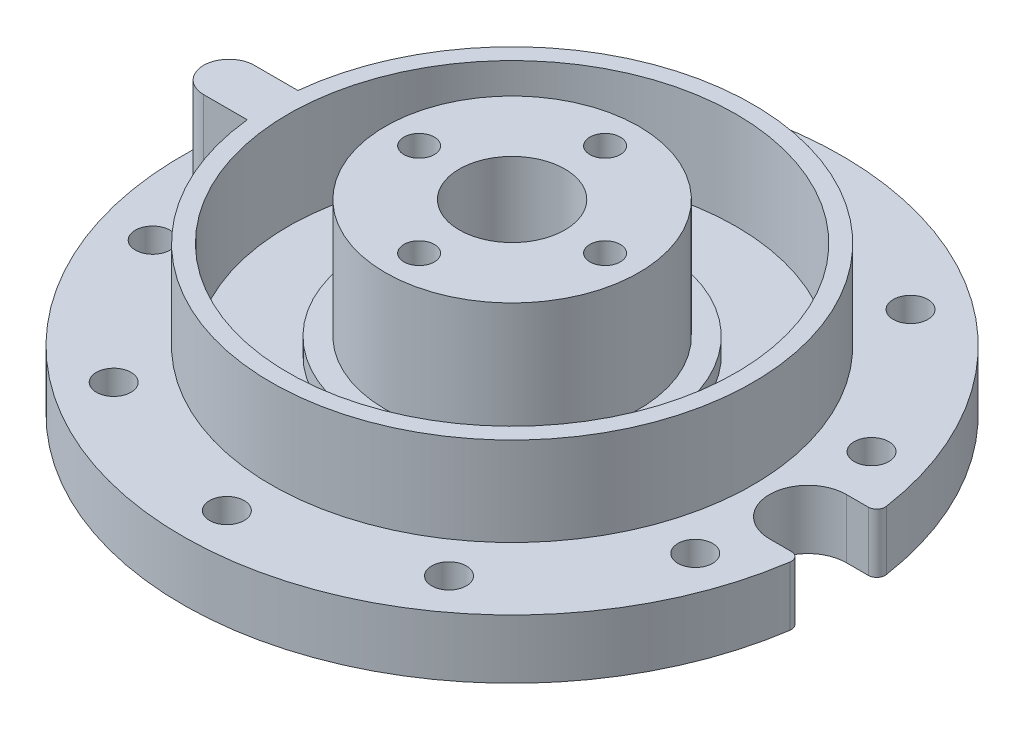
SolidWorks part; units mm, degrees
ref_plane "Front Plane" through (0, 0, 0) normal (0, 0, 1) x (1, 0, 0)
ref_plane "Top Plane" through (0, 0, 0) normal (0, 1, 0) x (1, 0, 0)
ref_plane "Right Plane" through (0, 0, 0) normal (1, 0, 0) x (0, 0, -1)
sketch "Sketch1" plane through (0, 0, 0) normal (0, 1, 0) x (1, 0, 0)
  circle A0 centre (0, 0) radius 39
  dimension "D1" = 78
extrude "Boss-Extrude1" add sketch "Sketch1" along normal blind 7
sketch "Sketch3" plane through (0, 7, 0) normal (0, 1, 0) x (1, 0, 0)
  circle A0 centre (0, 0) radius 17.5
  dimension "D1" = 35
extrude "Boss-Extrude2" add sketch "Sketch3" along normal blind 1
sketch "Sketch4" plane through (0, 8, 0) normal (0, 1, 0) x (1, 0, 0)
  circle A0 centre (0, 0) radius 15
  dimension "D1" = 30
extrude "Boss-Extrude3" add sketch "Sketch4" along normal blind 14 contours A0
sketch "Sketch5" plane through (0, 22, 0) normal (0, 1, 0) x (1, 0, 0)
  circle A0 centre (0, 0) radius 6.25
  circle A1 centre (0, 11) radius 1.8
  circle A2 centre (11, 0) radius 1.8
  circle A3 centre (0, -11) radius 1.8
  circle A4 centre (-11, 0) radius 1.8
  dimension "D1" = 12.5
  dimension "D3" = 3.6
  dimension "D2" = 11
  dimension "D4" = 4
extrude "Cut-Extrude1" cut sketch "Sketch5" against normal through all
hole_wizard "CSK for M4 Countersunk Flat Head Screw1" positions "3DSketch1" profile "Sketch6" countersink size "M4" standard "ISO" end condition through all
sketch3d "3DSketch1"
  line L0 (11, 0, 0) -> (11, 22, 0) construction
  line L1 (0, 0, -11) -> (0, 22, -11) construction
  line L2 (-11, 0, 0) -> (-11, 22, 0) construction
  line L3 (0, 0, 11) -> (0, 22, 11) construction
  point P0 (11, 0, 0)
  point P4 (0, 0, -11)
  point P8 (-11, 0, 0)
  point P12 (0, 0, 11)
sketch "Sketch6" plane through (11, 0, 0) normal (1, 0, 0) x (0, 0, -1)
  line L0 (0, 0) -> (0, 22)
  line L1 (0, 22) -> (1.75, 22)
  line L2 (1.75, 22) -> (1.75, 2.8)
  line L3 (1.75, 2.8) -> (4.55, 0)
  line L5 (4.55, 0) -> (0, 0)
  line L6 (-1.75, 2.8) -> (-4.55, 0) construction
  line L11 (0, -6.35) -> (0, 107.95) construction
  dimension "Thru Hole Dia." = 3.5
  dimension "Thru Hole Depth" = 22
  dimension "Near C'Sink Dia." = 9.1
  dimension "Near C'Sink Angle" = 90
sketch "Sketch7" plane through (0, 7, 0) normal (0, 1, 0) x (1, 0, 0)
  circle A0 centre (0, 0) radius 26.5
  circle A1 centre (0, 0) radius 28.5
  dimension "D1" = 53
  dimension "D2" = 2
extrude "Boss-Extrude4" add sketch "Sketch7" along normal blind 10.5
sketch "Sketch8" plane through (0, 7, 0) normal (0, 1, 0) x (1, 0, 0)
  circle A0 centre (0, 0) radius 17.5 construction
  circle A1 centre (0, 0) radius 26.5
  circle A2 centre (0, 0) radius 26.5
  circle A3 centre (0, 0) radius 17.5
  dimension "D1" = 0
extrude "Cut-Extrude2" cut sketch "Sketch8" against normal blind 1
sketch "Sketch9" plane through (0, 7, 0) normal (0, 1, 0) x (1, 0, 0)
  line L0 (0, 0) -> (0, 33.75) construction
  circle A0 centre (0, 33.75) radius 2.05
  circle A1 centre (19.8378, 27.3043) radius 2.05
  circle A2 centre (32.0982, 10.4293) radius 2.05
  circle A3 centre (32.0982, -10.4293) radius 2.05
  circle A4 centre (19.8378, -27.3043) radius 2.05
  circle A5 centre (0, -33.75) radius 2.05
  circle A6 centre (-19.8378, -27.3043) radius 2.05
  circle A7 centre (-32.0982, -10.4293) radius 2.05
  circle A8 centre (-32.0982, 10.4293) radius 2.05
  circle A9 centre (-19.8378, 27.3043) radius 2.05
  point P3 (0, 0)
  dimension "D2" = 4.1
  dimension "D1" = 33.75
  dimension "D3" = 10
extrude "Cut-Extrude3" cut sketch "Sketch9" against normal through all
sketch "Sketch10" plane through (0, 7, 0) normal (0, 1, 0) x (1, 0, 0)
  line L0 (-33.5, 0) -> (0, 0) construction
  line L1 (-33.5, 3) -> (-28.3417, 3)
  line L2 (-33.5, -3) -> (-28.3417, -3)
  arc A0 (-33.5, 3) -> (-33.5, -3) centre (-33.5, 0) ccw
  circle A1 centre (0, 0) radius 28.5 construction
  arc A2 (-28.3417, 3) -> (-28.3417, -3) centre (0, 0) ccw
  dimension "D2" = 6
  dimension "D1" = 33.5
extrude "Boss-Extrude5" add sketch "Sketch10" along normal up to surface (10.5 mm away) up to face at (0, 17.5, 28.5)
sketch "Sketch11" plane through (0, 7, 0) normal (0, 1, 0) x (1, 0, 0)
  line L0 (0, 0) -> (35, 0) construction
  line L1 (35, 4.55) -> (38.7337, 4.55)
  line L2 (35, -4.55) -> (38.7337, -4.55)
  arc A0 (35, 4.55) -> (35, -4.55) centre (35, 0) ccw
  circle A1 centre (0, 0) radius 39 construction
  arc A2 (38.7337, -4.55) -> (38.7337, 4.55) centre (0, 0) ccw
  dimension "D1" = 9.1
  dimension "D2" = 35
extrude "Cut-Extrude4" cut sketch "Sketch11" against normal through all contours L1 A2 L2 A0
fillet "Fillet1" radius 1 2 edges at (38.7337, 3.5, 4.55) (38.7337, 3.5, -4.55)
